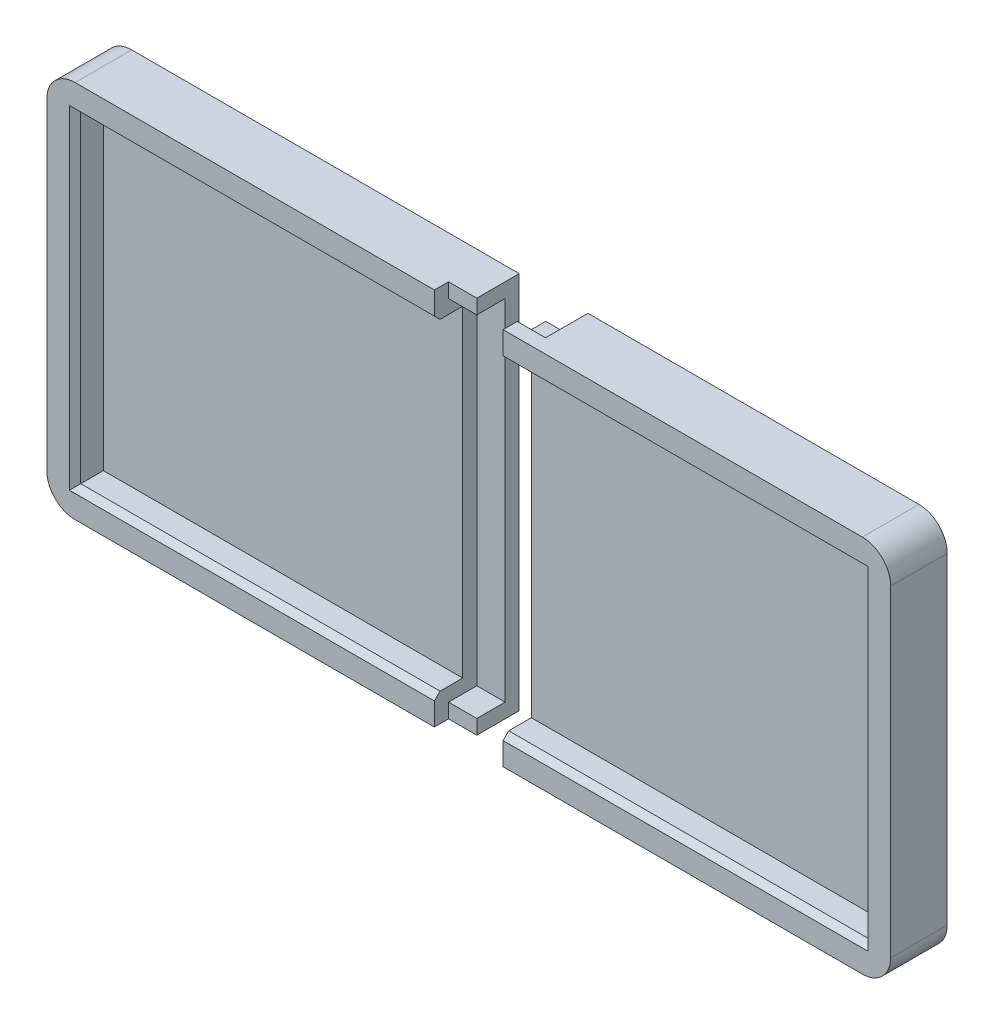
SolidWorks part; units mm, degrees
ref_plane "Front Plane" through (0, 0, 0) normal (0, 0, 1) x (1, 0, 0)
ref_plane "Top Plane" through (0, 0, 0) normal (0, 1, 0) x (1, 0, 0)
ref_plane "Right Plane" through (0, 0, 0) normal (1, 0, 0) x (0, 0, -1)
sketch "Sketch1" plane through (0, 0, 0) normal (0, 0, 1) x (1, 0, 0)
  line L1 (-80.645, 72.263) -> (80.645, 72.263)
  line L2 (-80.645, 72.263) -> (-80.645, -72.263)
  line L3 (-80.645, -72.263) -> (80.645, -72.263)
  line L5 (80.645, -84.963) -> (-93.345, -84.963)
  line L7 (80.645, 84.963) -> (-93.345, 84.963)
  line L8 (-93.345, -84.963) -> (-93.345, 84.963)
  line L13 (80.645, 72.263) -> (80.645, 84.963)
  line L14 (80.645, -72.263) -> (80.645, -84.963)
  point P4 (0, 72.263)
  point P6 (-80.645, 0)
  point P7 (0, 0)
  dimension "D1" = 12.7
  dimension "D2" = 12.7
  dimension "D3" = 161.29
  dimension "D4" = 144.526
extrude "Boss-Extrude1" add sketch "Sketch1" along normal blind 12.7
sketch "Sketch2" plane through (0, 0, 0) normal (0, 0, -1) x (-1, 0, 0)
  line L10 (93.345, 84.963) -> (-80.645, 84.963)
  line L12 (93.345, 84.963) -> (93.345, -84.963)
  line L13 (93.345, -84.963) -> (-80.645, -84.963)
  line L15 (-80.645, 84.963) -> (-80.645, -84.963)
  point P6 (0, 0)
extrude "Boss-Extrude2" add sketch "Sketch2" along normal blind 12.7
fillet "Fillet1" radius 12.7 2 edges at (-93.345, -84.963, 0) (-93.345, 84.963, 0)
fillet "Fillet2" radius 2.54 3 edges at (-80.645, 0, 12.7) (0, 72.263, 12.7) (0, -72.263, 12.7) profile chamfer
sketch "Sketch6" plane through (80.645, 0, 0) normal (1, 0, 0) x (0, 0, -1)
  line L0 (-6.35, 84.963) -> (12.7, 84.963)
  line L1 (12.7, 84.963) -> (12.7, 65.913)
  line L2 (12.7, 84.963) -> (12.7, -84.963) construction
  line L4 (6.35, 65.659) -> (6.35, 78.4452)
  line L5 (6.35, 78.4452) -> (-6.35, 78.4452)
  line L6 (-12.7, 84.963) -> (12.7, 84.963) construction
  line L7 (-6.35, 78.4452) -> (-6.35, 84.963)
  line L8 (55, 0) -> (-55, 0) construction
  line L9 (-6.35, -78.4452) -> (-6.35, -84.963)
  line L10 (6.35, -78.4452) -> (-6.35, -78.4452)
  line L11 (6.35, -65.659) -> (6.35, -78.4452)
  line L13 (12.7, -84.963) -> (12.7, -65.913)
  line L14 (-6.35, -84.963) -> (12.7, -84.963)
  line L15 (12.7, 65.913) -> (12.7, -65.913)
  line L16 (6.35, 65.659) -> (6.35, -65.659)
  dimension "D1" = 19.05
  dimension "D2" = 19.05
extrude "Boss-Extrude5" add sketch "Sketch6" along normal blind 12.7
ref_plane "Plane2" through (0, 0, 0) normal (0, 1, 0) x (1, 0, 0)
sketch "Sketch7" plane through (0, 0, 0) normal (0, 0, 1) x (1, 0, 0)
  line L0 (80.645, 84.963) -> (-80.645, 84.963) construction
  line L1 (111.4821, 84.963) -> (285.4721, 84.963)
  line L2 (111.4821, 84.963) -> (111.4821, -84.963)
  line L3 (111.4821, -84.963) -> (285.4721, -84.963)
  line L4 (285.4721, 84.963) -> (285.4721, -84.963)
  line L5 (-80.645, -84.963) -> (80.645, -84.963) construction
  line L7 (111.4821, 72.263) -> (272.7721, 72.263)
  line L8 (111.4821, 72.263) -> (111.4821, -72.263)
  line L9 (111.4821, -72.263) -> (272.7721, -72.263)
  line L10 (272.7721, 72.263) -> (272.7721, -72.263)
  dimension "D1" = 173.99
  dimension "D2" = 12.7
  dimension "D3" = 12.7
  dimension "D4" = 12.7
extrude "Boss-Extrude6" add sketch "Sketch7" along normal blind 12.7 separate body contours L7 L10 L9 L2 L3 L4 L1
sketch "Sketch8" plane through (0, 0, 0) normal (0, 0, -1) x (-1, 0, 0)
  line L1 (-285.4721, 84.963) -> (-111.4821, 84.963)
  line L2 (-285.4721, 84.963) -> (-285.4721, -84.963)
  line L3 (-285.4721, -84.963) -> (-111.4821, -84.963)
  line L4 (-111.4821, 84.963) -> (-111.4821, -84.963)
extrude "Boss-Extrude7" add sketch "Sketch8" along normal blind 12.7
sketch "Sketch9" plane through (111.4821, 0, 0) normal (-1, 0, 0) x (0, 0, 1)
  line L0 (-12.7, 84.963) -> (6.35, 84.963)
  line L1 (12.7, 84.963) -> (-12.7, 84.963) construction
  line L2 (6.35, 84.963) -> (6.35, 78.613)
  line L3 (6.35, 78.613) -> (-6.4542, 78.613)
  line L4 (-12.7, 84.963) -> (-12.7, -84.963)
  line L5 (-12.7, -84.963) -> (6.35, -84.963)
  line L6 (12.7, -84.963) -> (-12.7, -84.963) construction
  line L7 (6.35, -84.963) -> (6.35, -78.613)
  line L8 (6.35, -78.613) -> (-6.4542, -78.613)
  line L9 (-6.4542, -78.613) -> (-6.4542, 78.613)
  dimension "D1" = 6.35
  dimension "D2" = 19.05
  dimension "D3" = 19.05
  dimension "D4" = 6.35
extrude "Cut-Extrude1" cut sketch "Sketch9" against normal blind 12.7
chamfer "Chamfer1" distance 2.54 angle 45 3 edges at (192.1271, -72.263, 12.7) (272.7721, 0, 12.7) (192.1271, 72.263, 12.7)
fillet "Fillet4" radius 12.7 2 edges at (285.4721, -84.963, 0) (285.4721, 84.963, 0)
